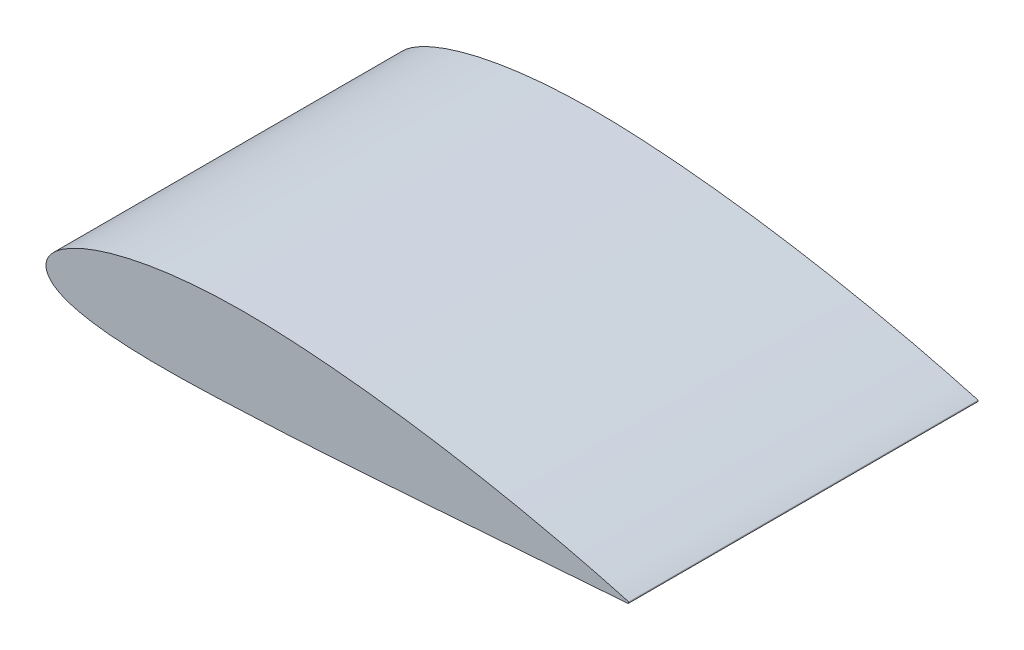
SolidWorks part; units mm, degrees
ref_plane "前视基准面" through (0, 0, 0) normal (0, 0, 1) x (1, 0, 0)
ref_plane "上视基准面" through (0, 0, 0) normal (0, 1, 0) x (1, 0, 0)
ref_plane "右视基准面" through (0, 0, 0) normal (1, 0, 0) x (0, 0, -1)
other "Configuration Table"
curve "Curve1"
  spline degree 3 poles (1.0008, -0.0016, 0) (1.0011, 0.0014, 0) (0.9997, 0.0017, 0) (0.999, 0.0019, 0) (0.9978, 0.0022, 0) (0.9961, 0.0027, 0) (0.9939, 0.0033, 0) (0.9913, 0.004, 0) (0.9882, 0.0049, 0) (0.9846, 0.0059, 0) (0.9805, 0.007, 0) (0.9759, 0.0082, 0) (0.9709, 0.0096, 0) (0.9655, 0.011, 0) (0.9595, 0.0126, 0) (0.9532, 0.0143, 0) (0.9463, 0.016, 0) (0.9391, 0.0179, 0) (0.9314, 0.0198, 0) (0.9233, 0.0219, 0) (0.9148, 0.024, 0) (0.9058, 0.0262, 0) (0.8965, 0.0284, 0) (0.8868, 0.0307, 0) (0.8767, 0.0331, 0) (0.8662, 0.0355, 0) (0.8553, 0.038, 0) (0.8441, 0.0404, 0) (0.8326, 0.043, 0) (0.8207, 0.0455, 0) (0.8085, 0.0481, 0) (0.796, 0.0507, 0) (0.7832, 0.0532, 0) (0.7701, 0.0558, 0) (0.7567, 0.0584, 0) (0.7431, 0.061, 0) (0.7292, 0.0635, 0) (0.7151, 0.066, 0) (0.7008, 0.0685, 0) (0.6863, 0.071, 0) (0.6715, 0.0734, 0) (0.6566, 0.0757, 0) (0.6416, 0.078, 0) (0.6263, 0.0803, 0) (0.611, 0.0824, 0) (0.5955, 0.0845, 0) (0.58, 0.0866, 0) (0.5643, 0.0885, 0) (0.5486, 0.0904, 0) (0.5328, 0.0921, 0) (0.517, 0.0938, 0) (0.5011, 0.0954, 0) (0.4852, 0.0968, 0) (0.4694, 0.0981, 0) (0.4536, 0.0994, 0) (0.4378, 0.1004, 0) (0.4221, 0.1014, 0) (0.4064, 0.1023, 0) (0.3907, 0.103, 0) (0.375, 0.1035, 0) (0.3595, 0.1038, 0) (0.344, 0.1039, 0) (0.3287, 0.1039, 0) (0.3136, 0.1036, 0) (0.2987, 0.1032, 0) (0.284, 0.1026, 0) (0.2695, 0.1017, 0) (0.2553, 0.1007, 0) (0.2413, 0.0996, 0) (0.2275, 0.0982, 0) (0.2141, 0.0967, 0) (0.201, 0.095, 0) (0.1881, 0.0931, 0) (0.1756, 0.091, 0) (0.1635, 0.0889, 0) (0.1517, 0.0865, 0) (0.1403, 0.0841, 0) (0.1292, 0.0815, 0) (0.1186, 0.0787, 0) (0.1083, 0.0759, 0) (0.0985, 0.0729, 0) (0.0891, 0.0699, 0) (0.0801, 0.0667, 0) (0.0716, 0.0635, 0) (0.0635, 0.0602, 0) (0.0558, 0.0568, 0) (0.0487, 0.0534, 0) (0.042, 0.0499, 0) (0.0358, 0.0464, 0) (0.03, 0.0429, 0) (0.0248, 0.0393, 0) (0.02, 0.0357, 0) (0.0158, 0.0321, 0) (0.012, 0.0285, 0) (0.0087, 0.0249, 0) (0.0059, 0.0213, 0) (0.0037, 0.0177, 0) (0.0019, 0.0141, 0) (0.0006, 0.0106, 0) (-0.0001, 0.007, 0) (-0.0004, 0.0035, 0) (-0.0001, 0, 0) (0.0007, -0.0034, 0) (0.0019, -0.0067, 0) (0.0037, -0.0099, 0) (0.0059, -0.013, 0) (0.0086, -0.0159, 0) (0.0118, -0.0187, 0) (0.0154, -0.0213, 0) (0.0195, -0.0239, 0) (0.0241, -0.0263, 0) (0.0291, -0.0286, 0) (0.0345, -0.0307, 0) (0.0404, -0.0328, 0) (0.0467, -0.0347, 0) (0.0534, -0.0365, 0) (0.0605, -0.0381, 0) (0.0681, -0.0397, 0) (0.076, -0.0411, 0) (0.0843, -0.0424, 0) (0.0931, -0.0436, 0) (0.1021, -0.0446, 0) (0.1116, -0.0455, 0) (0.1214, -0.0464, 0) (0.1315, -0.0471, 0) (0.142, -0.0477, 0) (0.1528, -0.0481, 0) (0.164, -0.0485, 0) (0.1754, -0.0488, 0) (0.1871, -0.049, 0) (0.1991, -0.049, 0) (0.2114, -0.049, 0) (0.224, -0.0489, 0) (0.2368, -0.0487, 0) (0.2498, -0.0485, 0) (0.2631, -0.0482, 0) (0.2766, -0.0478, 0) (0.2903, -0.0473, 0) (0.3043, -0.0468, 0) (0.3184, -0.0462, 0) (0.3326, -0.0456, 0) (0.3471, -0.045, 0) (0.3616, -0.0443, 0) (0.3764, -0.0437, 0) (0.3912, -0.043, 0) (0.4063, -0.0422, 0) (0.4216, -0.0415, 0) (0.4369, -0.0407, 0) (0.4524, -0.0398, 0) (0.4678, -0.0389, 0) (0.4834, -0.038, 0) (0.4989, -0.037, 0) (0.5145, -0.036, 0) (0.53, -0.035, 0) (0.5455, -0.034, 0) (0.561, -0.0329, 0) (0.5764, -0.0319, 0) (0.5918, -0.0308, 0) (0.6071, -0.0297, 0) (0.6223, -0.0286, 0) (0.6373, -0.0276, 0) (0.6523, -0.0265, 0) (0.6671, -0.0254, 0) (0.6817, -0.0244, 0) (0.6962, -0.0233, 0) (0.7105, -0.0223, 0) (0.7246, -0.0213, 0) (0.7385, -0.0203, 0) (0.7521, -0.0193, 0) (0.7656, -0.0184, 0) (0.7787, -0.0174, 0) (0.7916, -0.0165, 0) (0.8042, -0.0156, 0) (0.8165, -0.0147, 0) (0.8285, -0.0139, 0) (0.8402, -0.013, 0) (0.8515, -0.0122, 0) (0.8626, -0.0114, 0) (0.8732, -0.0107, 0) (0.8835, -0.0099, 0) (0.8934, -0.0092, 0) (0.9029, -0.0086, 0) (0.912, -0.0079, 0) (0.9208, -0.0073, 0) (0.9291, -0.0067, 0) (0.9369, -0.0061, 0) (0.9444, -0.0056, 0) (0.9514, -0.0051, 0) (0.9579, -0.0046, 0) (0.964, -0.0042, 0) (0.9697, -0.0038, 0) (0.9748, -0.0034, 0) (0.9795, -0.0031, 0) (0.9837, -0.0027, 0) (0.9874, -0.0025, 0) (0.9907, -0.0022, 0) (0.9934, -0.002, 0) (0.9957, -0.0019, 0) (0.9974, -0.0017, 0) (0.9987, -0.0017, 0) (0.9994, -0.0016, 0) (1.0008, -0.0016, 0) (1.0011, 0.0014, 0) (0.9997, 0.0017, 0) knots -0.002013 -0.001648 -0.001526 0 0.000122 0.000488 0.001097 0.001949 0.003043 0.004377 0.005952 0.007763 0.009812 0.012093 0.014607 0.017349 0.020317 0.02351 0.026921 0.03055 0.034391 0.038442 0.042698 0.047154 0.051806 0.05665 0.061681 0.066894 0.072284 0.077844 0.083571 0.089457 0.095498 0.101686 0.108017 0.114484 0.12108 0.127799 0.134634 0.141579 0.148625 0.155768 0.162999 0.170311 0.177698 0.185151 0.192664 0.200228 0.207837 0.215482 0.223157 0.230853 0.238564 0.24628 0.253996 0.261702 0.269392 0.277058 0.284692 0.292287 0.299903 0.30751 0.315056 0.322535 0.329938 0.337259 0.34449 0.351625 0.358657 0.365578 0.372384 0.379068 0.385622 0.392042 0.398322 0.404456 0.410439 0.416264 0.421929 0.427428 0.432757 0.437911 0.442887 0.44768 0.452289 0.45671 0.460941 0.46498 0.468825 0.472477 0.475935 0.479199 0.482272 0.485156 0.487856 0.490379 0.492731 0.494925 0.496976 0.4989 0.500721 0.502465 0.504164 0.505852 0.507539 0.509238 0.510981 0.512798 0.514716 0.516755 0.518931 0.521259 0.523748 0.526406 0.529236 0.532245 0.535432 0.538799 0.542347 0.546075 0.549982 0.554065 0.558323 0.562754 0.567354 0.57212 0.577048 0.582136 0.587379 0.592774 0.598316 0.603999 0.609821 0.615777 0.621861 0.628068 0.634393 0.640832 0.647378 0.654027 0.660772 0.667609 0.67453 0.681531 0.688604 0.695745 0.702947 0.710248 0.717664 0.72512 0.73261 0.740126 0.747661 0.755207 0.762758 0.770307 0.777845 0.785366 0.792861 0.800325 0.807749 0.815126 0.822449 0.82971 0.836903 0.84402 0.851054 0.857997 0.864844 0.871587 0.878219 0.884734 0.891125 0.897385 0.903508 0.909489 0.915319 0.920994 0.926509 0.931856 0.93703 0.942027 0.946841 0.951466 0.955899 0.960133 0.964166 0.967992 0.971607 0.975008 0.97819 0.981151 0.983887 0.986396 0.988674 0.990718 0.992528 0.994101 0.995434 0.996527 0.997378 0.997987 0.998352 0.998474 1 1.000122 1.000488 1.001097 periodic
sketch "Sketch2" plane through (0, 0, 0) normal (0, 0, 1) x (1, 0, 0)
  line L0 (182.4058, 1.4791) -> (32.4058, 1.4791) construction
  line L1 (32.4058, 1.4791) -> (32.4058, 28.2862) construction
  spline S1 degree 3 poles (182.508, 1.0083) (182.5515, 1.4514) (182.3441, 1.4941) (182.2367, 1.5273) (182.0541, 1.5756) (181.8004, 1.6467) (181.4739, 1.736) (181.0757, 1.8454) (180.6058, 1.9735) (180.0647, 2.1206) (179.4529, 2.2856) (178.771, 2.4686) (178.0195, 2.6688) (177.1991, 2.8854) (176.3106, 3.1183) (175.3546, 3.3664) (174.3321, 3.6293) (173.244, 3.9062) (172.0913, 4.196) (170.875, 4.4984) (169.5961, 4.812) (168.256, 5.1367) (166.8557, 5.4709) (165.3967, 5.8144) (163.8802, 6.1658) (162.3076, 6.5245) (160.6804, 6.8894) (159.0001, 7.2597) (157.2683, 7.6344) (155.4866, 8.0126) (153.6567, 8.3934) (151.7803, 8.776) (149.8593, 9.159) (147.8953, 9.5422) (145.8904, 9.9241) (143.8464, 10.304) (141.7653, 10.6812) (139.6492, 11.0544) (137.5, 11.4226) (135.3199, 11.7855) (133.111, 12.1419) (130.8754, 12.4907) (128.6154, 12.8312) (126.3331, 13.1627) (124.0309, 13.4841) (121.711, 13.7946) (119.3757, 14.0937) (117.0274, 14.3801) (114.6683, 14.6531) (112.301, 14.9123) (109.9277, 15.1563) (107.551, 15.3851) (105.173, 15.5971) (102.7965, 15.7924) (100.4236, 15.97) (98.0569, 16.1291) (95.6988, 16.2694) (93.345, 16.3909) (90.9929, 16.4914) (88.6447, 16.5629) (86.3099, 16.6067) (83.9959, 16.622) (81.7051, 16.6084) (79.4402, 16.5666) (77.2037, 16.4962) (74.9981, 16.3972) (72.8259, 16.2708) (70.6896, 16.116) (68.5915, 15.9346) (66.5339, 15.7259) (64.5192, 15.4915) (62.5496, 15.2314) (60.6273, 14.9468) (58.7544, 14.6383) (56.933, 14.307) (55.165, 13.9539) (53.4523, 13.5798) (51.7968, 13.1861) (50.2002, 12.7737) (48.6642, 12.344) (47.1903, 11.8981) (45.7801, 11.4374) (44.4349, 10.9631) (43.1559, 10.4767) (41.9445, 9.9791) (40.8018, 9.4719) (39.7288, 8.9564) (38.7264, 8.4337) (37.7954, 7.9052) (36.9368, 7.3718) (36.1508, 6.835) (35.4384, 6.2955) (34.7997, 5.7547) (34.2357, 5.2128) (33.746, 4.6714) (33.3313, 4.1305) (32.9918, 3.591) (32.7277, 3.0532) (32.5398, 2.5173) (32.4279, 1.9841) (32.3932, 1.454) (32.4348, 0.9303) (32.5507, 0.418) (32.7411, -0.0777) (33.0044, -0.554) (33.34, -1.0106) (33.7465, -1.4476) (34.2232, -1.8653) (34.7692, -2.2635) (35.3838, -2.6427) (36.0663, -3.0029) (36.8156, -3.3444) (37.6312, -3.6667) (38.5118, -3.9704) (39.4567, -4.255) (40.4648, -4.5209) (41.5348, -4.7682) (42.666, -4.9963) (43.8567, -5.2063) (45.1059, -5.3975) (46.4124, -5.5702) (47.7748, -5.7253) (49.1917, -5.8621) (50.6618, -5.9814) (52.1836, -6.0833) (53.7558, -6.1687) (55.3769, -6.237) (57.0454, -6.2899) (58.7598, -6.3268) (60.5185, -6.349) (62.3201, -6.3568) (64.1629, -6.3511) (66.0454, -6.3322) (67.966, -6.301) (69.9229, -6.2583) (71.9146, -6.2052) (73.9393, -6.1418) (75.9954, -6.0695) (78.0811, -5.9894) (80.1947, -5.9017) (82.3344, -5.8078) (84.4984, -5.7084) (86.6848, -5.6044) (88.8918, -5.4972) (91.1222, -5.3862) (93.3809, -5.2749) (95.6656, -5.1557) (97.9693, -5.0286) (100.2829, -4.895) (102.6043, -4.7551) (104.9313, -4.6101) (107.2616, -4.4602) (109.5931, -4.3068) (111.9235, -4.1494) (114.2505, -3.9898) (116.5719, -3.8276) (118.8855, -3.6639) (121.189, -3.4991) (123.4802, -3.3338) (125.7568, -3.1682) (128.0167, -3.0027) (130.2575, -2.8381) (132.4771, -2.6744) (134.6732, -2.5122) (136.8437, -2.3514) (138.9864, -2.1927) (141.0992, -2.0364) (143.1799, -1.8823) (145.2264, -1.7308) (147.2368, -1.5822) (149.2089, -1.4365) (151.1407, -1.2943) (153.0302, -1.1548) (154.8755, -1.0193) (156.6748, -0.8868) (158.4261, -0.7584) (160.1277, -0.6334) (161.7778, -0.5123) (163.3747, -0.3953) (164.9166, -0.2821) (166.4021, -0.1734) (167.8294, -0.0683) (169.1972, 0.032) (170.504, 0.1281) (171.7483, 0.2197) (172.9289, 0.3067) (174.0445, 0.389) (175.0939, 0.4668) (176.0759, 0.5396) (176.9896, 0.6072) (177.8338, 0.6702) (178.6078, 0.7278) (179.3106, 0.7802) (179.9415, 0.8274) (180.4999, 0.8692) (180.9851, 0.9055) (181.3965, 0.9367) (181.7338, 0.9615) (181.9962, 0.9824) (182.1846, 0.9945) (182.2964, 1.0062) (182.508, 1.0083) (182.5515, 1.4514) (182.3441, 1.4941) knots -0.002013 -0.001648 -0.001526 0 0.000122 0.000488 0.001097 0.001949 0.003043 0.004377 0.005952 0.007763 0.009812 0.012093 0.014607 0.017349 0.020317 0.02351 0.026921 0.03055 0.034391 0.038442 0.042698 0.047154 0.051806 0.05665 0.061681 0.066894 0.072284 0.077844 0.083571 0.089457 0.095498 0.101686 0.108017 0.114484 0.12108 0.127799 0.134634 0.141579 0.148625 0.155768 0.162999 0.170311 0.177698 0.185151 0.192664 0.200228 0.207837 0.215482 0.223157 0.230853 0.238564 0.24628 0.253996 0.261702 0.269392 0.277058 0.284692 0.292287 0.299903 0.30751 0.315056 0.322535 0.329938 0.337259 0.34449 0.351625 0.358657 0.365578 0.372384 0.379068 0.385622 0.392042 0.398322 0.404456 0.410439 0.416264 0.421929 0.427428 0.432757 0.437911 0.442887 0.44768 0.452289 0.45671 0.460941 0.46498 0.468825 0.472477 0.475935 0.479199 0.482272 0.485156 0.487856 0.490379 0.492731 0.494925 0.496976 0.4989 0.500721 0.502465 0.504164 0.505852 0.507539 0.509238 0.510981 0.512798 0.514716 0.516755 0.518931 0.521259 0.523748 0.526406 0.529236 0.532245 0.535432 0.538799 0.542347 0.546075 0.549982 0.554065 0.558323 0.562754 0.567354 0.57212 0.577048 0.582136 0.587379 0.592774 0.598316 0.603999 0.609821 0.615777 0.621861 0.628068 0.634393 0.640832 0.647378 0.654027 0.660772 0.667609 0.67453 0.681531 0.688604 0.695745 0.702947 0.710248 0.717664 0.72512 0.73261 0.740126 0.747661 0.755207 0.762758 0.770307 0.777845 0.785366 0.792861 0.800325 0.807749 0.815126 0.822449 0.82971 0.836903 0.84402 0.851054 0.857997 0.864844 0.871587 0.878219 0.884734 0.891125 0.897385 0.903508 0.909489 0.915319 0.920994 0.926509 0.931856 0.93703 0.942027 0.946841 0.951466 0.955899 0.960133 0.964166 0.967992 0.971607 0.975008 0.97819 0.981151 0.983887 0.986396 0.988674 0.990718 0.992528 0.994101 0.995434 0.996527 0.997378 0.997987 0.998352 0.998474 1 1.000122 1.000488 1.001097 only from (182.4058, 1.4791) to (182.4058, 1.4791)
  dimension "D1" = 150
extrude "Boss-Extrude1" add sketch "Sketch2" along normal blind 90
